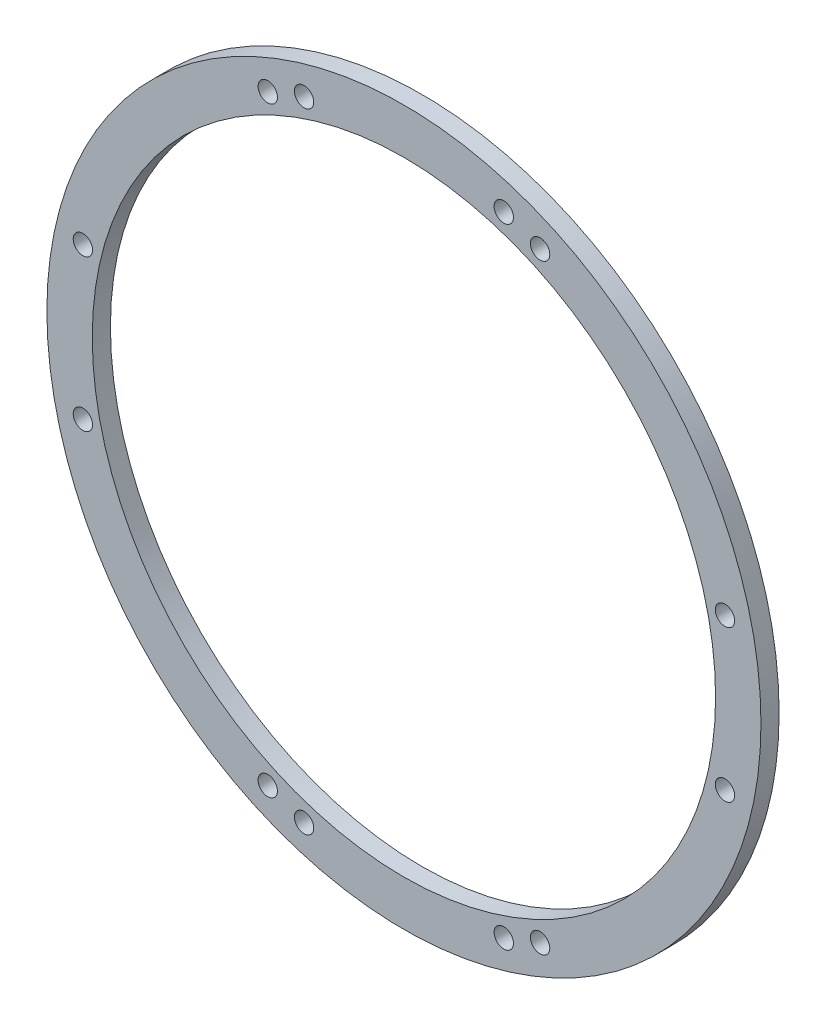
SolidWorks part; units mm, degrees
material "A-玻璃纤维"
ref_plane "前视基准面" through (0, 0, 0) normal (0, 0, 1) x (1, 0, 0)
ref_plane "上视基准面" through (0, 0, 0) normal (0, 1, 0) x (1, 0, 0)
ref_plane "右视基准面" through (0, 0, 0) normal (1, 0, 0) x (0, 0, -1)
other "Configuration Table"
sketch "草图1" plane through (0, 0, 0) normal (0, 0, 1) x (1, 0, 0)
  line L0 (0, 0) -> (0, 54.5) construction
  line L1 (0, 51.9423) -> (16.5, 51.9423) construction
  line L2 (0, 49.6387) -> (22.5, 49.6387) construction
  line L3 (0, 0) -> (54.5, 0) construction
  line L4 (53.0471, 0) -> (53.0471, 12.5) construction
  circle A0 centre (0, 0) radius 59
  circle A1 centre (0, 0) radius 51.5
  circle A2 centre (0, 0) radius 54.5 construction
  circle A3 centre (16.5, 51.9423) radius 1.6
  circle A4 centre (22.5, 49.6387) radius 1.6
  circle A5 centre (53.0471, 12.5) radius 1.6
  circle A6 centre (22.5, -49.6387) radius 1.6
  circle A7 centre (16.5, -51.9423) radius 1.6
  circle A8 centre (53.0471, -12.5) radius 1.6
  circle A9 centre (-16.5, -51.9423) radius 1.6
  circle A10 centre (-22.5, -49.6387) radius 1.6
  circle A11 centre (-53.0471, -12.5) radius 1.6
  circle A12 centre (-53.0471, 12.5) radius 1.6
  circle A13 centre (-22.5, 49.6387) radius 1.6
  circle A14 centre (-16.5, 51.9423) radius 1.6
  point P33 (13.1561, 1.4471)
  point P34 (0, 0)
  dimension "D1" = 118
  dimension "D2" = 103
  dimension "D3" = 109
  dimension "D6" = 3.2
  dimension "D7" = 3.2
  dimension "D9" = 3.2
  dimension "D4" = 16.5
  dimension "D5" = 22.5
  dimension "D8" = 12.5
extrude "凸台-拉伸1" add sketch "草图1" along normal blind 3
